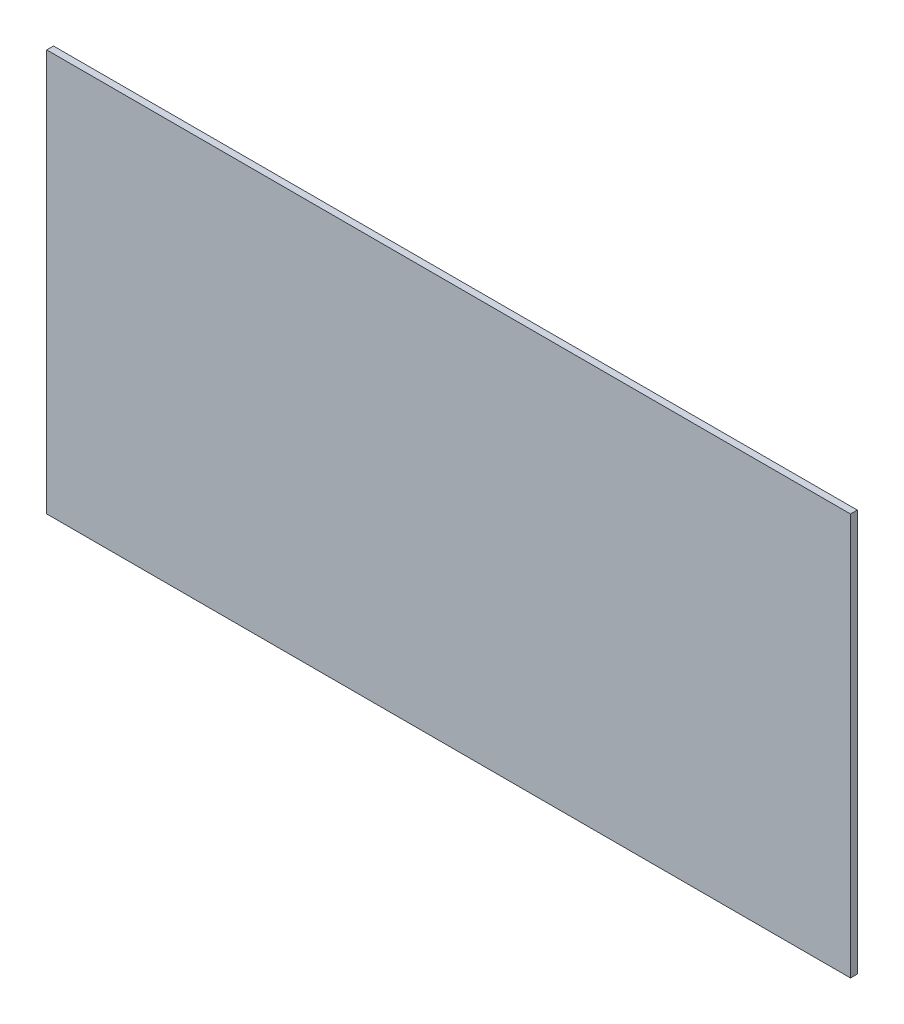
SolidWorks part; units mm, degrees
ref_plane "Plan de face" through (0, 0, 0) normal (0, 0, 1) x (1, 0, 0)
ref_plane "Plan de dessus" through (0, 0, 0) normal (0, 1, 0) x (1, 0, 0)
ref_plane "Plan de droite" through (0, 0, 0) normal (1, 0, 0) x (0, 0, -1)
sketch "Esquisse1" plane through (0, 0, 0) normal (0, 0, 1) x (1, 0, 0)
  line L1 (-134.6711, 118.8618) -> (221.3289, 118.8618)
  line L2 (-134.6711, 118.8618) -> (-134.6711, -59.1382)
  line L3 (-134.6711, -59.1382) -> (221.3289, -59.1382)
  line L4 (221.3289, 118.8618) -> (221.3289, -59.1382)
  dimension "D1" = 356
  dimension "D2" = 178
extrude "Boss.-Extru.1" add sketch "Esquisse1" along normal blind 3
